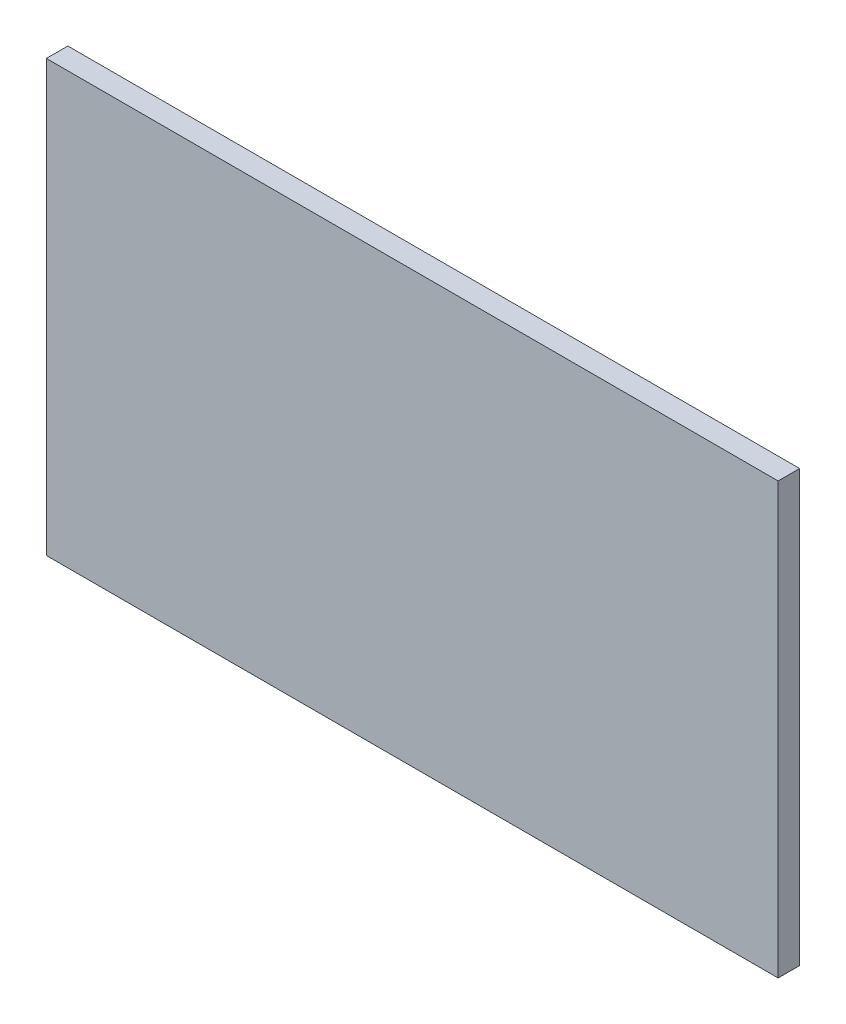
SolidWorks part; units mm, degrees
ref_plane "Plan de face" through (0, 0, 0) normal (0, 0, 1) x (1, 0, 0)
ref_plane "Plan de dessus" through (0, 0, 0) normal (0, 1, 0) x (1, 0, 0)
ref_plane "Plan de droite" through (0, 0, 0) normal (1, 0, 0) x (0, 0, -1)
sketch "Esquisse1" plane through (0, 0, 0) normal (0, 0, 1) x (1, 0, 0)
  line L1 (0, 0) -> (170, 0)
  line L2 (0, 0) -> (0, 100)
  line L3 (0, 100) -> (170, 100)
  line L4 (170, 0) -> (170, 100)
  dimension "D1" = 170
  dimension "D2" = 100
extrude "Boss.-Extru.1" add sketch "Esquisse1" along normal blind 5
